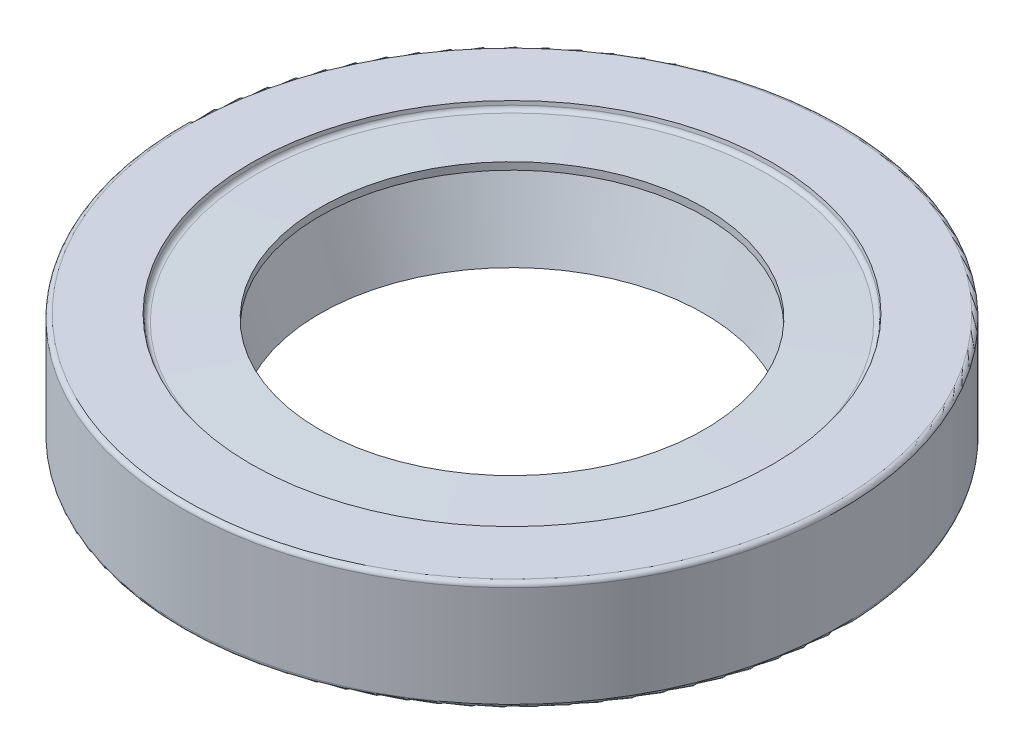
SolidWorks part; units mm, degrees
ref_plane "Plane1" through (0, 0, 0) normal (0, 0, 1) x (1, 0, 0)
ref_plane "Plane2" through (0, 0, 0) normal (0, 1, 0) x (1, 0, 0)
ref_plane "Plane3" through (0, 0, 0) normal (1, 0, 0) x (0, 0, -1)
revolve "Base-Revolve" add sketch "Sketch1" angle 360 about L0
sketch "Sketch1" plane through (0, 0, 0) normal (0, 0, 1) x (1, 0, 0)
  line L0 (0, 20.4322) -> (0, 0) construction
  line L1 (33, 0) -> (36, 0)
  line L2 (36, 0) -> (36, 12)
  line L3 (36, 12) -> (28.5, 12)
  line L4 (28.5, 12) -> (28.3589, 11.2)
  line L5 (28.3589, 11.2) -> (21, 11.52)
  line L6 (21, 11.52) -> (21, 10.72)
  line L7 (21, 10.72) -> (24.3558, 10.72)
  line L8 (24.3558, 10.72) -> (21, 1.5)
  line L9 (21, 1.5) -> (26.4545, 1.5)
  line L10 (26.4545, 1.5) -> (26.4545, 2.1667)
  line L11 (26.4545, 3.7667) -> (29.4895, 8.5667)
  line L12 (29.4895, 8.5667) -> (31.4895, 8.5667)
  line L13 (31.4895, 8.5667) -> (33, 0)
  line L14 (26.4545, 3.3667) -> (26.4545, 3.7667)
  arc A0 (26.4545, 3.3667) -> (26.4545, 2.1667) centre (26.4545, 2.7667) cw construction
  arc A1 (26.4545, 3.3667) -> (26.4545, 2.1667) centre (26.4545, 2.7667) ccw
  dimension "D9" = 0.6
  dimension "D1" = 1.5
  dimension "D2" = 5.4545
  dimension "_d" = 42
  dimension "_dd" = 72
  dimension "D5" = 3
  dimension "D6" = 0.6667
  dimension "D7" = 0.4
  dimension "D8" = 4.8
  dimension "D10" = 2
  dimension "D11" = 70
  dimension "D13" = 100
  dimension "b" = 12
  dimension "D15" = 7.5
  dimension "D16" = 0.8
  dimension "D17" = 0.8
  dimension "D18" = 0.48
  dimension "D19" = 42
  dimension "D20" = 80
fillet "Fillet1" radius 0.48 3 edges at (0, 12, 36) (0, 0, 36) (0, 1.5, 26.4545)
fillet "Fillet2" radius 0.48 1 edges at (0, 11.2, 28.3589)
fillet "Fillet3" radius 0.8 1 edges at (0, 10.72, 24.3558)
sketch "Skica1" plane through (0, 0, 0) normal (0, 0, 1) x (1, 0, 0)
  line L0 (0, 0) -> (0, 12) construction
  line L1 (28.5, 12) -> (-28.5, 12) construction
  circle A0 centre (26.4545, 2.7667) radius 0.6
  arc A1 (26.4545, 3.3667) -> (26.4545, 2.1667) centre (26.4545, 2.7667) ccw construction
  circle A2 centre (26.4545, 2.7667) radius 0.59
  dimension "D1" = 0.01
revolve "Otočit kolem osy1" add sketch "Skica1" angle 360 about L0
equation "\"D2@Sketch1\" =  ( \"_dd@Sketch1\" - \"_d@Sketch1\" )  / 5.5"
equation "\"D6@Sketch1\" = \"b@Sketch1\" / 18"
equation "\"D7@Sketch1\" = \"b@Sketch1\" / 30"
equation "\"D8@Sketch1\" =  \"b@Sketch1\" / 2.5"
equation "\"D9@Sketch1\" = \"b@Sketch1\" / 20"
equation "\"D1@Sketch1\" = \"b@Sketch1\" / 8"
equation "\"D5@Sketch1\" =  ( \"_dd@Sketch1\" - \"_d@Sketch1\" )  / 10"
equation "\"D10@Sketch1\" =  ( \"_dd@Sketch1\" - \"_d@Sketch1\" )  / 15"
equation "\"D17@Sketch1\" = \"b@Sketch1\" / 15"
equation "\"D18@Sketch1\" = \"b@Sketch1\" / 25"
equation "\"D16@Sketch1\" = \"b@Sketch1\" / 15"
equation "\"D15@Sketch1\" =  ( \"_dd@Sketch1\" - \"_d@Sketch1\" )  / 4"
equation "\"D1@Fillet3\" = \"b@Sketch1\" / 15"
equation "\"D1@Fillet2\" = \"b@Sketch1\" / 25"
equation "\"D1@Fillet1\" = \"b@Sketch1\" / 25"
equation "\"D19@Sketch1\" = \"_d@Sketch1\""
